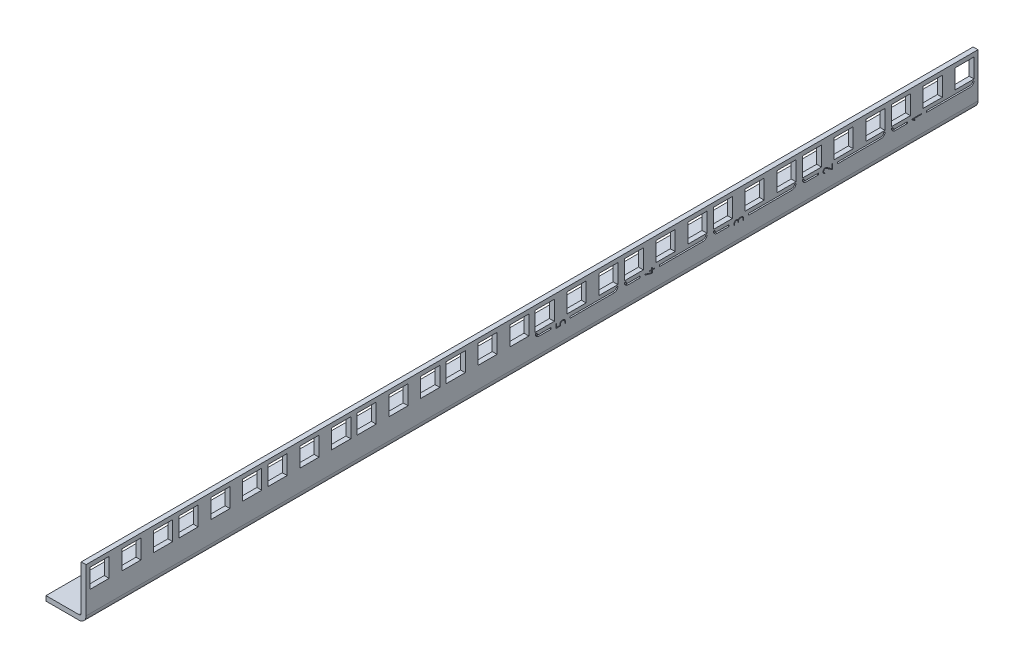
SolidWorks part; units mm, degrees
ref_plane "Front Plane" through (0, 0, 0) normal (0, 0, 1) x (1, 0, 0)
ref_plane "Top Plane" through (0, 0, 0) normal (0, 1, 0) x (1, 0, 0)
ref_plane "Right Plane" through (0, 0, 0) normal (1, 0, 0) x (0, 0, -1)
ref_plane "Plane1" through (0, 25.781, 0) normal (0, 1, 0) x (1, 0, 0)
sketch "Sketch1" plane through (0, 25.781, 0) normal (0, 1, 0) x (1, 0, 0)
  line L0 (-25.4, -222.631) -> (25.4, -222.631)
  line L1 (25.4, -222.631) -> (25.4, 222.631)
  line L2 (25.4, 222.631) -> (-25.4, 222.631)
  line L3 (-25.4, 222.631) -> (-25.4, -222.631)
extrude "Boss-Extrude1" add sketch "Sketch1" against normal blind 25.781
sketch "Sketch2" plane through (0, 0, -222.631) normal (0, 0, -1) x (-1, 0, 0)
  line L0 (25.4, 25.781) -> (-22.987, 25.781)
  line L1 (-22.987, 25.781) -> (-22.987, 2.413)
  line L2 (-22.987, 2.413) -> (25.4, 2.413)
  line L3 (25.4, 2.413) -> (25.4, 25.781)
extrude "Cut-Extrude1" cut sketch "Sketch2" against normal through all
sketch "Sketch3" plane through (0, 0, 0) normal (0, -1, 0) x (1, 0, 0)
  line L0 (-13.5001, -198.0311) -> (-8.7503, -198.0311)
  line L1 (-8.7503, -190.0809) -> (-13.5001, -190.0809)
  arc A0 (-8.7503, -198.0311) -> (-8.7503, -190.0809) centre (-8.7503, -194.056) ccw
  arc A1 (-13.5001, -190.0809) -> (-13.5001, -198.0311) centre (-13.5001, -194.056) ccw
extrude "Cut-Extrude2" cut sketch "Sketch3" against normal through all
sketch "Sketch4" plane through (22.987, 0, 0) normal (-1, 0, 0) x (0, 0, 1)
  line L0 (220.6625, 23.6474) -> (211.1375, 23.6474)
  line L1 (211.1375, 23.6474) -> (211.1375, 14.1224)
  line L2 (211.1375, 14.1224) -> (220.6625, 14.1224)
  line L3 (220.6625, 14.1224) -> (220.6625, 23.6474)
extrude "Cut-Extrude3" cut sketch "Sketch4" against normal through all
sketch "Sketch5" plane through (22.987, 0, 0) normal (-1, 0, 0) x (0, 0, 1)
  line L0 (204.7875, 23.6474) -> (195.2625, 23.6474)
  line L1 (195.2625, 23.6474) -> (195.2625, 14.1224)
  line L2 (195.2625, 14.1224) -> (204.7875, 14.1224)
  line L3 (204.7875, 14.1224) -> (204.7875, 23.6474)
extrude "Cut-Extrude4" cut sketch "Sketch5" against normal through all
sketch "Sketch6" plane through (22.987, 0, 0) normal (-1, 0, 0) x (0, 0, 1)
  line L0 (188.9125, 23.6474) -> (179.3875, 23.6474)
  line L1 (179.3875, 23.6474) -> (179.3875, 14.1224)
  line L2 (179.3875, 14.1224) -> (188.9125, 14.1224)
  line L3 (188.9125, 14.1224) -> (188.9125, 23.6474)
extrude "Cut-Extrude5" cut sketch "Sketch6" against normal through all
sketch "Sketch7" plane through (22.987, 0, 0) normal (-1, 0, 0) x (0, 0, 1)
  line L0 (176.2125, 23.6474) -> (166.6875, 23.6474)
  line L1 (166.6875, 23.6474) -> (166.6875, 14.1224)
  line L2 (166.6875, 14.1224) -> (176.2125, 14.1224)
  line L3 (176.2125, 14.1224) -> (176.2125, 23.6474)
extrude "Cut-Extrude6" cut sketch "Sketch7" against normal through all
sketch "Sketch8" plane through (22.987, 0, 0) normal (-1, 0, 0) x (0, 0, 1)
  line L0 (160.3375, 23.6474) -> (150.8125, 23.6474)
  line L1 (150.8125, 23.6474) -> (150.8125, 14.1224)
  line L2 (150.8125, 14.1224) -> (160.3375, 14.1224)
  line L3 (160.3375, 14.1224) -> (160.3375, 23.6474)
extrude "Cut-Extrude7" cut sketch "Sketch8" against normal through all
sketch "Sketch9" plane through (22.987, 0, 0) normal (-1, 0, 0) x (0, 0, 1)
  line L0 (144.4625, 23.6474) -> (134.9375, 23.6474)
  line L1 (134.9375, 23.6474) -> (134.9375, 14.1224)
  line L2 (134.9375, 14.1224) -> (144.4625, 14.1224)
  line L3 (144.4625, 14.1224) -> (144.4625, 23.6474)
extrude "Cut-Extrude8" cut sketch "Sketch9" against normal through all
sketch "Sketch10" plane through (22.987, 0, 0) normal (-1, 0, 0) x (0, 0, 1)
  line L0 (131.7625, 23.6474) -> (122.2375, 23.6474)
  line L1 (122.2375, 23.6474) -> (122.2375, 14.1224)
  line L2 (122.2375, 14.1224) -> (131.7625, 14.1224)
  line L3 (131.7625, 14.1224) -> (131.7625, 23.6474)
extrude "Cut-Extrude9" cut sketch "Sketch10" against normal through all
sketch "Sketch11" plane through (22.987, 0, 0) normal (-1, 0, 0) x (0, 0, 1)
  line L0 (115.8875, 23.6474) -> (106.3625, 23.6474)
  line L1 (106.3625, 23.6474) -> (106.3625, 14.1224)
  line L2 (106.3625, 14.1224) -> (115.8875, 14.1224)
  line L3 (115.8875, 14.1224) -> (115.8875, 23.6474)
extrude "Cut-Extrude10" cut sketch "Sketch11" against normal through all
sketch "Sketch12" plane through (22.987, 0, 0) normal (-1, 0, 0) x (0, 0, 1)
  line L0 (100.0125, 23.6474) -> (90.4875, 23.6474)
  line L1 (90.4875, 23.6474) -> (90.4875, 14.1224)
  line L2 (90.4875, 14.1224) -> (100.0125, 14.1224)
  line L3 (100.0125, 14.1224) -> (100.0125, 23.6474)
extrude "Cut-Extrude11" cut sketch "Sketch12" against normal through all
sketch "Sketch13" plane through (22.987, 0, 0) normal (-1, 0, 0) x (0, 0, 1)
  line L0 (87.3125, 23.6474) -> (77.7875, 23.6474)
  line L1 (77.7875, 23.6474) -> (77.7875, 14.1224)
  line L2 (77.7875, 14.1224) -> (87.3125, 14.1224)
  line L3 (87.3125, 14.1224) -> (87.3125, 23.6474)
extrude "Cut-Extrude12" cut sketch "Sketch13" against normal through all
sketch "Sketch14" plane through (22.987, 0, 0) normal (-1, 0, 0) x (0, 0, 1)
  line L0 (71.4375, 23.6474) -> (61.9125, 23.6474)
  line L1 (61.9125, 23.6474) -> (61.9125, 14.1224)
  line L2 (61.9125, 14.1224) -> (71.4375, 14.1224)
  line L3 (71.4375, 14.1224) -> (71.4375, 23.6474)
extrude "Cut-Extrude13" cut sketch "Sketch14" against normal through all
sketch "Sketch15" plane through (22.987, 0, 0) normal (-1, 0, 0) x (0, 0, 1)
  line L0 (55.5625, 23.6474) -> (46.0375, 23.6474)
  line L1 (46.0375, 23.6474) -> (46.0375, 14.1224)
  line L2 (46.0375, 14.1224) -> (55.5625, 14.1224)
  line L3 (55.5625, 14.1224) -> (55.5625, 23.6474)
extrude "Cut-Extrude14" cut sketch "Sketch15" against normal through all
sketch "Sketch16" plane through (22.987, 0, 0) normal (-1, 0, 0) x (0, 0, 1)
  line L0 (42.8625, 23.6474) -> (33.3375, 23.6474)
  line L1 (33.3375, 23.6474) -> (33.3375, 14.1224)
  line L2 (33.3375, 14.1224) -> (42.8625, 14.1224)
  line L3 (42.8625, 14.1224) -> (42.8625, 23.6474)
extrude "Cut-Extrude15" cut sketch "Sketch16" against normal through all
sketch "Sketch17" plane through (22.987, 0, 0) normal (-1, 0, 0) x (0, 0, 1)
  line L0 (26.9875, 23.6474) -> (17.4625, 23.6474)
  line L1 (17.4625, 23.6474) -> (17.4625, 14.1224)
  line L2 (17.4625, 14.1224) -> (26.9875, 14.1224)
  line L3 (26.9875, 14.1224) -> (26.9875, 23.6474)
extrude "Cut-Extrude16" cut sketch "Sketch17" against normal through all
sketch "Sketch18" plane through (22.987, 0, 0) normal (-1, 0, 0) x (0, 0, 1)
  line L0 (11.1125, 23.6474) -> (1.5875, 23.6474)
  line L1 (1.5875, 23.6474) -> (1.5875, 14.1224)
  line L2 (1.5875, 14.1224) -> (11.1125, 14.1224)
  line L3 (11.1125, 14.1224) -> (11.1125, 23.6474)
extrude "Cut-Extrude17" cut sketch "Sketch18" against normal through all
sketch "Sketch19" plane through (22.987, 0, 0) normal (-1, 0, 0) x (0, 0, 1)
  line L0 (-1.5875, 23.6474) -> (-11.1125, 23.6474)
  line L1 (-11.1125, 23.6474) -> (-11.1125, 14.1224)
  line L2 (-11.1125, 14.1224) -> (-1.5875, 14.1224)
  line L3 (-1.5875, 14.1224) -> (-1.5875, 23.6474)
extrude "Cut-Extrude18" cut sketch "Sketch19" against normal through all
sketch "Sketch20" plane through (22.987, 0, 0) normal (-1, 0, 0) x (0, 0, 1)
  line L0 (-17.4625, 23.6474) -> (-26.9875, 23.6474)
  line L1 (-26.9875, 23.6474) -> (-26.9875, 14.1224)
  line L2 (-26.9875, 14.1224) -> (-17.4625, 14.1224)
  line L3 (-17.4625, 14.1224) -> (-17.4625, 23.6474)
extrude "Cut-Extrude19" cut sketch "Sketch20" against normal through all
sketch "Sketch21" plane through (22.987, 0, 0) normal (-1, 0, 0) x (0, 0, 1)
  line L0 (-33.3375, 23.6474) -> (-42.8625, 23.6474)
  line L1 (-42.8625, 23.6474) -> (-42.8625, 14.1224)
  line L2 (-42.8625, 14.1224) -> (-33.3375, 14.1224)
  line L3 (-33.3375, 14.1224) -> (-33.3375, 23.6474)
extrude "Cut-Extrude20" cut sketch "Sketch21" against normal through all
sketch "Sketch22" plane through (22.987, 0, 0) normal (-1, 0, 0) x (0, 0, 1)
  line L0 (-46.0375, 23.6474) -> (-55.5625, 23.6474)
  line L1 (-55.5625, 23.6474) -> (-55.5625, 14.1224)
  line L2 (-55.5625, 14.1224) -> (-46.0375, 14.1224)
  line L3 (-46.0375, 14.1224) -> (-46.0375, 23.6474)
extrude "Cut-Extrude21" cut sketch "Sketch22" against normal through all
sketch "Sketch23" plane through (22.987, 0, 0) normal (-1, 0, 0) x (0, 0, 1)
  line L0 (-61.9125, 23.6474) -> (-71.4375, 23.6474)
  line L1 (-71.4375, 23.6474) -> (-71.4375, 14.1224)
  line L2 (-71.4375, 14.1224) -> (-61.9125, 14.1224)
  line L3 (-61.9125, 14.1224) -> (-61.9125, 23.6474)
extrude "Cut-Extrude22" cut sketch "Sketch23" against normal through all
sketch "Sketch24" plane through (22.987, 0, 0) normal (-1, 0, 0) x (0, 0, 1)
  line L0 (-77.7875, 23.6474) -> (-87.3125, 23.6474)
  line L1 (-87.3125, 23.6474) -> (-87.3125, 14.1224)
  line L2 (-87.3125, 14.1224) -> (-77.7875, 14.1224)
  line L3 (-77.7875, 14.1224) -> (-77.7875, 23.6474)
extrude "Cut-Extrude23" cut sketch "Sketch24" against normal through all
sketch "Sketch25" plane through (22.987, 0, 0) normal (-1, 0, 0) x (0, 0, 1)
  line L0 (-90.4875, 23.6474) -> (-100.0125, 23.6474)
  line L1 (-100.0125, 23.6474) -> (-100.0125, 14.1224)
  line L2 (-100.0125, 14.1224) -> (-90.4875, 14.1224)
  line L3 (-90.4875, 14.1224) -> (-90.4875, 23.6474)
extrude "Cut-Extrude24" cut sketch "Sketch25" against normal through all
sketch "Sketch26" plane through (22.987, 0, 0) normal (-1, 0, 0) x (0, 0, 1)
  line L0 (-106.3625, 23.6474) -> (-115.8875, 23.6474)
  line L1 (-115.8875, 23.6474) -> (-115.8875, 14.1224)
  line L2 (-115.8875, 14.1224) -> (-106.3625, 14.1224)
  line L3 (-106.3625, 14.1224) -> (-106.3625, 23.6474)
extrude "Cut-Extrude25" cut sketch "Sketch26" against normal through all
sketch "Sketch27" plane through (22.987, 0, 0) normal (-1, 0, 0) x (0, 0, 1)
  line L0 (-122.2375, 23.6474) -> (-131.7625, 23.6474)
  line L1 (-131.7625, 23.6474) -> (-131.7625, 14.1224)
  line L2 (-131.7625, 14.1224) -> (-122.2375, 14.1224)
  line L3 (-122.2375, 14.1224) -> (-122.2375, 23.6474)
extrude "Cut-Extrude26" cut sketch "Sketch27" against normal through all
sketch "Sketch28" plane through (22.987, 0, 0) normal (-1, 0, 0) x (0, 0, 1)
  line L0 (-134.9375, 23.6474) -> (-144.4625, 23.6474)
  line L1 (-144.4625, 23.6474) -> (-144.4625, 14.1224)
  line L2 (-144.4625, 14.1224) -> (-134.9375, 14.1224)
  line L3 (-134.9375, 14.1224) -> (-134.9375, 23.6474)
extrude "Cut-Extrude27" cut sketch "Sketch28" against normal through all
sketch "Sketch29" plane through (22.987, 0, 0) normal (-1, 0, 0) x (0, 0, 1)
  line L0 (-150.8125, 23.6474) -> (-160.3375, 23.6474)
  line L1 (-160.3375, 23.6474) -> (-160.3375, 14.1224)
  line L2 (-160.3375, 14.1224) -> (-150.8125, 14.1224)
  line L3 (-150.8125, 14.1224) -> (-150.8125, 23.6474)
extrude "Cut-Extrude28" cut sketch "Sketch29" against normal through all
sketch "Sketch30" plane through (22.987, 0, 0) normal (-1, 0, 0) x (0, 0, 1)
  line L0 (-166.6875, 23.6474) -> (-176.2125, 23.6474)
  line L1 (-176.2125, 23.6474) -> (-176.2125, 14.1224)
  line L2 (-176.2125, 14.1224) -> (-166.6875, 14.1224)
  line L3 (-166.6875, 14.1224) -> (-166.6875, 23.6474)
extrude "Cut-Extrude29" cut sketch "Sketch30" against normal through all
sketch "Sketch31" plane through (22.987, 0, 0) normal (-1, 0, 0) x (0, 0, 1)
  line L0 (-179.3875, 23.6474) -> (-188.9125, 23.6474)
  line L1 (-188.9125, 23.6474) -> (-188.9125, 14.1224)
  line L2 (-188.9125, 14.1224) -> (-179.3875, 14.1224)
  line L3 (-179.3875, 14.1224) -> (-179.3875, 23.6474)
extrude "Cut-Extrude30" cut sketch "Sketch31" against normal through all
sketch "Sketch32" plane through (22.987, 0, 0) normal (-1, 0, 0) x (0, 0, 1)
  line L0 (-195.2625, 23.6474) -> (-204.7875, 23.6474)
  line L1 (-204.7875, 23.6474) -> (-204.7875, 14.1224)
  line L2 (-204.7875, 14.1224) -> (-195.2625, 14.1224)
  line L3 (-195.2625, 14.1224) -> (-195.2625, 23.6474)
extrude "Cut-Extrude31" cut sketch "Sketch32" against normal through all
sketch "Sketch33" plane through (22.987, 0, 0) normal (-1, 0, 0) x (0, 0, 1)
  line L0 (-211.1375, 23.6474) -> (-220.6625, 23.6474)
  line L1 (-220.6625, 23.6474) -> (-220.6625, 14.1224)
  line L2 (-220.6625, 14.1224) -> (-211.1375, 14.1224)
  line L3 (-211.1375, 14.1224) -> (-211.1375, 23.6474)
extrude "Cut-Extrude32" cut sketch "Sketch33" against normal through all
sketch "Sketch34" plane through (0, 2.413, 0) normal (0, 1, 0) x (-1, 0, 0)
  line L0 (13.5001, 198.0311) -> (8.7503, 198.0311)
  line L1 (8.7503, 190.0809) -> (13.5001, 190.0809)
  arc A0 (8.7503, 198.0311) -> (8.7503, 190.0809) centre (8.7503, 194.056) ccw
  arc A1 (13.5001, 190.0809) -> (13.5001, 198.0311) centre (13.5001, 194.056) ccw
extrude "Cut-Extrude33" cut sketch "Sketch34" against normal through all
sketch "Sketch35" plane through (25.4, 0, 0) normal (1, 0, 0) x (0, 0, -1)
  line L0 (61.1315, 11.8809) -> (61.1315, 12.2306)
  line L1 (61.1315, 12.2306) -> (60.031, 12.2306)
  line L2 (60.031, 12.2306) -> (60.031, 12.9703)
  line L3 (60.031, 12.9703) -> (59.6666, 12.9703)
  line L4 (59.6666, 12.9703) -> (59.6666, 12.2306)
  line L5 (59.6666, 12.2306) -> (58.6471, 12.2306)
  line L6 (58.6471, 12.2306) -> (58.6471, 11.8809)
  line L7 (58.6471, 11.8809) -> (59.6666, 11.8809)
  line L8 (59.6666, 11.8809) -> (59.6666, 10.8394)
  line L9 (59.6666, 10.8394) -> (56.3726, 11.8368)
  line L10 (56.3726, 11.8368) -> (56.3689, 11.4761)
  line L11 (56.3689, 11.4761) -> (59.7182, 10.4713)
  line L12 (59.7182, 10.4713) -> (60.031, 10.4713)
  line L13 (60.031, 10.4713) -> (60.031, 11.8809)
  line L14 (60.031, 11.8809) -> (61.1315, 11.8809)
extrude "Cut-Extrude34" cut sketch "Sketch35" against normal blind 0.762
sketch "Sketch36" plane through (25.4, 0, 0) normal (1, 0, 0) x (0, 0, -1)
  line L0 (16.3428, 10.5431) -> (16.6814, 10.5431)
  line L1 (13.899, 10.9332) -> (12.2539, 10.9332)
  line L2 (12.2539, 10.9332) -> (12.2539, 12.5747)
  line L3 (12.2539, 12.5747) -> (11.9189, 12.5747)
  line L4 (11.9189, 12.5747) -> (11.9189, 10.5946)
  line L5 (11.9189, 10.5946) -> (14.234, 10.5946)
  spline S0 degree 3 poles (16.3428, 10.5431) (16.3428, 10.8445) (16.3687, 11.1477) (16.3359, 11.4474) (16.3241, 11.5549) (16.2955, 11.6626) (16.2478, 11.7598) (16.1999, 11.8573) (16.1312, 11.9465) (16.0508, 12.0197) (15.9605, 12.1018) (15.8543, 12.1688) (15.7419, 12.2167) (15.6292, 12.2647) (15.5076, 12.2943) (15.3859, 12.3078) (15.2464, 12.3232) (15.1023, 12.3213) (14.9651, 12.2916) (14.8612, 12.269) (14.7594, 12.2294) (14.6684, 12.1744) (14.577, 12.1192) (14.4936, 12.0464) (14.4296, 11.9609) (14.3732, 11.8857) (14.3299, 11.7996) (14.2997, 11.7105) (14.2545, 11.5774) (14.2363, 11.4345) (14.2341, 11.2939) (14.2323, 11.1774) (14.2329, 11.0608) (14.2331, 10.9443) (14.2334, 10.8277) (14.234, 10.7112) (14.234, 10.5946) knots 0 0 0 0 0.000904 0.000904 0.000904 0.001232 0.001232 0.001232 0.001561 0.001561 0.001561 0.001931 0.001931 0.001931 0.002301 0.002301 0.002301 0.002725 0.002725 0.002725 0.003045 0.003045 0.003045 0.003369 0.003369 0.003369 0.003651 0.003651 0.003651 0.004075 0.004075 0.004075 0.004423 0.004423 0.004423 0.004772 0.004772 0.004772 0.004772
  spline S1 degree 3 poles (15.213, 12.652) (15.4155, 12.652) (15.6221, 12.6283) (15.8143, 12.5643) (15.9431, 12.5214) (16.0675, 12.4588) (16.1758, 12.377) (16.2844, 12.2948) (16.379, 12.1912) (16.453, 12.0769) (16.5425, 11.9387) (16.6077, 11.7824) (16.6461, 11.6222) (16.7299, 11.2722) (16.6814, 10.903) (16.6814, 10.5431) knots 0 0 0 0 0.000608 0.000608 0.000608 0.001013 0.001013 0.001013 0.001421 0.001421 0.001421 0.001914 0.001914 0.001914 0.003 0.003 0.003 0.003
  spline S2 degree 3 poles (13.899, 10.9332) (13.899, 11.1689) (13.8803, 11.4071) (13.9151, 11.6402) (13.9339, 11.7666) (13.9717, 11.8922) (14.0302, 12.0058) (14.0888, 12.1199) (14.1698, 12.2242) (14.2639, 12.3114) (14.3547, 12.3956) (14.4594, 12.4671) (14.5713, 12.5203) (14.695, 12.579) (14.83, 12.6165) (14.9656, 12.6355) (15.0474, 12.6469) (15.1303, 12.652) (15.213, 12.652) knots 0 0 0 0 0.000707 0.000707 0.000707 0.001092 0.001092 0.001092 0.001479 0.001479 0.001479 0.001852 0.001852 0.001852 0.002264 0.002264 0.002264 0.002511 0.002511 0.002511 0.002511
extrude "Cut-Extrude35" cut sketch "Sketch36" against normal blind 0.762
sketch "Sketch37" plane through (25.4, 0, 0) normal (1, 0, 0) x (0, 0, -1)
  line L0 (150.0314, 12.8931) -> (149.6947, 12.8931)
  line L1 (149.6947, 12.8931) -> (149.6947, 10.8432)
  line L2 (149.6947, 10.8432) -> (146.9162, 12.7321)
  line L3 (146.3525, 10.4076) -> (146.3525, 10.748)
  line L4 (149.6983, 10.4368) -> (150.0314, 10.4222)
  line L5 (150.0314, 10.4222) -> (150.0314, 12.8931)
  spline S0 degree 3 poles (146.3525, 10.4076) (146.1386, 10.4564) (145.9244, 10.5328) (145.743, 10.6562) (145.6457, 10.7224) (145.5567, 10.804) (145.4858, 10.8977) (145.4146, 10.9919) (145.3602, 11.1006) (145.3253, 11.2133) (145.2819, 11.3538) (145.267, 11.5039) (145.2692, 11.651) (145.2721, 11.8451) (145.2993, 12.044) (145.3712, 12.2243) (145.4116, 12.3258) (145.4676, 12.4229) (145.5382, 12.5062) (145.6091, 12.5899) (145.6963, 12.6621) (145.7921, 12.7155) (145.8817, 12.7654) (145.9806, 12.8004) (146.081, 12.822) (146.2419, 12.8566) (146.4116, 12.8637) (146.5746, 12.8402) (146.6928, 12.8231) (146.8099, 12.7865) (146.9162, 12.7321) knots 0 0 0 0 0.000658 0.000658 0.000658 0.001008 0.001008 0.001008 0.001359 0.001359 0.001359 0.001796 0.001796 0.001796 0.002376 0.002376 0.002376 0.002699 0.002699 0.002699 0.003024 0.003024 0.003024 0.003327 0.003327 0.003327 0.003815 0.003815 0.003815 0.004169 0.004169 0.004169 0.004169
  spline S1 degree 3 poles (145.829, 12.3404) (145.7581, 12.2492) (145.6979, 12.1462) (145.6632, 12.036) (145.6176, 11.8912) (145.5982, 11.7364) (145.6025, 11.5847) (145.6051, 11.4931) (145.6201, 11.4004) (145.6508, 11.3141) (145.6817, 11.2273) (145.7298, 11.1449) (145.7901, 11.0752) (145.8448, 11.0121) (145.9101, 10.9576) (145.9802, 10.9122) (146.094, 10.8385) (146.2224, 10.7863) (146.3525, 10.748) knots 0 0 0 0 0.000347 0.000347 0.000347 0.0008 0.0008 0.0008 0.001073 0.001073 0.001073 0.001349 0.001349 0.001349 0.001597 0.001597 0.001597 0.002002 0.002002 0.002002 0.002002
  spline S2 degree 3 poles (149.6983, 10.4368) (149.3691, 10.6598) (149.0399, 10.8829) (148.7106, 11.1059) (148.3814, 11.3289) (148.0521, 11.5519) (147.7229, 11.7749) (147.534, 11.9028) (147.345, 12.0308) (147.1561, 12.1588) (146.9665, 12.2872) (146.7804, 12.4438) (146.5573, 12.4954) (146.4525, 12.5197) (146.3418, 12.5271) (146.2351, 12.513) (146.1476, 12.5014) (146.0609, 12.474) (145.9823, 12.4337) (145.9291, 12.4064) (145.88, 12.3717) (145.829, 12.3404) knots 0 0 0 0 0.001193 0.001193 0.001193 0.002386 0.002386 0.002386 0.00307 0.00307 0.00307 0.00376 0.00376 0.00376 0.004075 0.004075 0.004075 0.004334 0.004334 0.004334 0.004507 0.004507 0.004507 0.004507
extrude "Cut-Extrude36" cut sketch "Sketch37" against normal blind 0.762
sketch "Sketch38" plane through (25.4, 0, 0) normal (1, 0, 0) x (0, 0, -1)
  line L0 (105.2428, 10.6277) -> (105.5814, 10.6277)
  line L1 (100.8189, 10.6204) -> (101.1539, 10.6204)
  line L2 (102.7843, 10.9443) -> (103.1229, 10.9443)
  spline S0 degree 3 poles (105.2428, 10.6277) (105.2428, 10.9248) (105.274, 11.2247) (105.2319, 11.5187) (105.217, 11.623) (105.1849, 11.7267) (105.1352, 11.8196) (105.0854, 11.9127) (105.0166, 11.9972) (104.9375, 12.0671) (104.8627, 12.1332) (104.777, 12.1886) (104.6859, 12.2295) (104.5845, 12.275) (104.4745, 12.3036) (104.3642, 12.3174) (104.1886, 12.3393) (104.0063, 12.3309) (103.8339, 12.2909) (103.7244, 12.2655) (103.6167, 12.2242) (103.5205, 12.1659) (103.4408, 12.1176) (103.3666, 12.0571) (103.3068, 11.9856) (103.2466, 11.9137) (103.1998, 11.8287) (103.17, 11.7398) (103.1367, 11.6405) (103.1229, 11.5339) (103.1229, 11.4291) (103.1229, 11.2675) (103.1229, 11.1059) (103.1229, 10.9443) knots 0 0 0 0 0.000891 0.000891 0.000891 0.001209 0.001209 0.001209 0.001528 0.001528 0.001528 0.001828 0.001828 0.001828 0.002163 0.002163 0.002163 0.002698 0.002698 0.002698 0.003037 0.003037 0.003037 0.003317 0.003317 0.003317 0.0036 0.0036 0.0036 0.003915 0.003915 0.003915 0.004396 0.004396 0.004396 0.004396
  spline S1 degree 3 poles (104.1976, 12.6667) (104.3916, 12.6667) (104.5898, 12.64) (104.7722, 12.574) (104.9062, 12.5254) (105.034, 12.4541) (105.1448, 12.3644) (105.2558, 12.2745) (105.3531, 12.163) (105.4234, 12.0386) (105.4867, 11.9266) (105.5301, 11.8021) (105.5544, 11.6758) (105.6206, 11.3327) (105.5814, 10.9772) (105.5814, 10.6277) knots 0 0 0 0 0.000582 0.000582 0.000582 0.001008 0.001008 0.001008 0.001436 0.001436 0.001436 0.001819 0.001819 0.001819 0.002863 0.002863 0.002863 0.002863
  spline S2 degree 3 poles (102.9389, 12.0447) (102.9781, 12.1341) (103.035, 12.2173) (103.1032, 12.2871) (103.171, 12.3566) (103.251, 12.415) (103.3355, 12.4629) (103.4794, 12.5443) (103.6398, 12.5994) (103.8021, 12.6308) (103.9321, 12.6559) (104.0652, 12.6667) (104.1976, 12.6667) knots 0 0 0 0 0.000293 0.000293 0.000293 0.000583 0.000583 0.000583 0.001079 0.001079 0.001079 0.001474 0.001474 0.001474 0.001474
  spline S3 degree 3 poles (100.8189, 10.6204) (100.8189, 11.0186) (100.765, 11.4358) (100.8932, 11.8129) (100.9307, 11.923) (100.9858, 12.029) (101.0571, 12.1208) (101.1286, 12.2127) (101.2182, 12.2924) (101.3161, 12.3555) (101.4134, 12.4181) (101.5201, 12.4684) (101.631, 12.5012) (101.7635, 12.5404) (101.9064, 12.5415) (102.0442, 12.5327) (102.175, 12.5244) (102.3076, 12.5061) (102.4309, 12.4616) (102.5342, 12.4243) (102.6322, 12.3675) (102.7166, 12.2971) (102.8027, 12.2253) (102.8771, 12.1382) (102.9389, 12.0447) knots 0 0 0 0 0.001195 0.001195 0.001195 0.001536 0.001536 0.001536 0.001878 0.001878 0.001878 0.002216 0.002216 0.002216 0.002624 0.002624 0.002624 0.00301 0.00301 0.00301 0.003335 0.003335 0.003335 0.003665 0.003665 0.003665 0.003665
  spline S4 degree 3 poles (102.7843, 10.9443) (102.7843, 11.1408) (102.7995, 11.3384) (102.7795, 11.5339) (102.7709, 11.6181) (102.7494, 11.7024) (102.7134, 11.779) (102.6773, 11.8559) (102.6254, 11.9266) (102.5644, 11.9858) (102.5078, 12.0407) (102.443, 12.0885) (102.3732, 12.1252) (102.309, 12.1591) (102.2379, 12.1836) (102.1657, 12.1911) (102.0226, 12.2059) (101.8747, 12.2156) (101.7342, 12.1849) (101.6597, 12.1687) (101.5874, 12.1367) (101.5247, 12.0933) (101.4625, 12.0502) (101.4078, 11.9955) (101.3609, 11.9362) (101.2939, 11.8514) (101.2399, 11.7543) (101.205, 11.6521) (101.1705, 11.5507) (101.1539, 11.442) (101.1539, 11.335) (101.1537, 11.0968) (101.1539, 10.8586) (101.1539, 10.6204) knots 0 0 0 0 0.00059 0.00059 0.00059 0.000846 0.000846 0.000846 0.001103 0.001103 0.001103 0.001341 0.001341 0.001341 0.001561 0.001561 0.001561 0.001991 0.001991 0.001991 0.002218 0.002218 0.002218 0.002443 0.002443 0.002443 0.002765 0.002765 0.002765 0.003083 0.003083 0.003083 0.003784 0.003784 0.003784 0.003784
extrude "Cut-Extrude37" cut sketch "Sketch38" against normal blind 0.762
sketch "Sketch39" plane through (25.4, 0, 0) normal (1, 0, 0) x (0, 0, -1)
  line L0 (191.0996, 11.3191) -> (190.3175, 11.9323)
  line L1 (190.3175, 11.9323) -> (194.4778, 11.9323)
  line L2 (194.4778, 11.9323) -> (194.4814, 12.2665)
  line L3 (194.4814, 12.2665) -> (189.719, 12.2665)
  line L4 (189.719, 12.2665) -> (189.719, 11.9507)
  line L5 (189.719, 11.9507) -> (191.0996, 10.9005)
  line L6 (191.0996, 10.9005) -> (191.0996, 11.3191)
extrude "Cut-Extrude38" cut sketch "Sketch39" against normal blind 0.762
sketch "Sketch40" plane through (25.4, 0, 0) normal (1, 0, 0) x (0, 0, -1)
  line L0 (42.8752, 13.4112) -> (42.1132, 13.4112)
  line L1 (40.9702, 12.2682) -> (19.0627, 12.2682)
  line L2 (19.0627, 12.2682) -> (19.0627, 11.5062)
  line L3 (19.0627, 11.5062) -> (40.9702, 11.5062)
  arc A0 (40.9702, 11.5062) -> (42.8752, 13.4112) centre (40.9702, 13.4112) ccw
  arc A1 (42.1132, 13.4112) -> (40.9702, 12.2682) centre (40.9702, 13.4112) cw
extrude "Cut-Extrude39" cut sketch "Sketch40" against normal blind 0.762
sketch "Sketch41" plane through (25.4, 0, 0) normal (1, 0, 0) x (0, 0, -1)
  line L0 (53.9877, 12.2725) -> (47.8557, 12.2725)
  line L1 (46.8122, 13.4112) -> (46.0502, 13.4112)
  line L2 (47.9552, 11.5062) -> (53.9877, 11.5062)
  line L3 (53.9877, 11.5062) -> (53.9877, 12.2725)
  arc A0 (47.8557, 12.2725) -> (46.8122, 13.4112) centre (47.9552, 13.4112) cw
  arc A1 (46.0502, 13.4112) -> (47.9552, 11.5062) centre (47.9552, 13.4112) ccw
extrude "Cut-Extrude40" cut sketch "Sketch41" against normal blind 0.762
sketch "Sketch42" plane through (25.4, 0, 0) normal (1, 0, 0) x (0, 0, -1)
  line L0 (131.7752, 13.4112) -> (131.0132, 13.4112)
  line L1 (129.8702, 12.2682) -> (107.9627, 12.2682)
  line L2 (107.9627, 12.2682) -> (107.9627, 11.5062)
  line L3 (107.9627, 11.5062) -> (129.8702, 11.5062)
  arc A0 (129.8702, 11.5062) -> (131.7752, 13.4112) centre (129.8702, 13.4112) ccw
  arc A1 (131.0132, 13.4112) -> (129.8702, 12.2682) centre (129.8702, 13.4112) cw
extrude "Cut-Extrude41" cut sketch "Sketch42" against normal blind 0.762
sketch "Sketch43" plane through (25.4, 0, 0) normal (1, 0, 0) x (0, 0, -1)
  line L0 (142.8877, 12.2725) -> (136.7557, 12.2725)
  line L1 (135.7122, 13.4112) -> (134.9502, 13.4112)
  line L2 (136.8552, 11.5062) -> (142.8877, 11.5062)
  line L3 (142.8877, 11.5062) -> (142.8877, 12.2725)
  arc A0 (136.7557, 12.2725) -> (135.7122, 13.4112) centre (136.8552, 13.4112) cw
  arc A1 (134.9502, 13.4112) -> (136.8552, 11.5062) centre (136.8552, 13.4112) ccw
extrude "Cut-Extrude42" cut sketch "Sketch43" against normal blind 0.762
sketch "Sketch44" plane through (25.4, 0, 0) normal (1, 0, 0) x (0, 0, -1)
  line L0 (187.3377, 12.2725) -> (181.2057, 12.2725)
  line L1 (180.1622, 13.4112) -> (179.4002, 13.4112)
  line L2 (181.3052, 11.5062) -> (187.3377, 11.5062)
  line L3 (187.3377, 11.5062) -> (187.3377, 12.2725)
  arc A0 (181.2057, 12.2725) -> (180.1622, 13.4112) centre (181.3052, 13.4112) cw
  arc A1 (179.4002, 13.4112) -> (181.3052, 11.5062) centre (181.3052, 13.4112) ccw
extrude "Cut-Extrude43" cut sketch "Sketch44" against normal blind 0.762
sketch "Sketch45" plane through (25.4, 0, 0) normal (1, 0, 0) x (0, 0, -1)
  line L0 (176.2252, 13.4112) -> (175.4632, 13.4112)
  line L1 (174.3202, 12.2682) -> (152.4127, 12.2682)
  line L2 (152.4127, 12.2682) -> (152.4127, 11.5062)
  line L3 (152.4127, 11.5062) -> (174.3202, 11.5062)
  arc A0 (174.3202, 11.5062) -> (176.2252, 13.4112) centre (174.3202, 13.4112) ccw
  arc A1 (175.4632, 13.4112) -> (174.3202, 12.2682) centre (174.3202, 13.4112) cw
extrude "Cut-Extrude44" cut sketch "Sketch45" against normal blind 0.762
sketch "Sketch46" plane through (25.4, 0, 0) normal (1, 0, 0) x (0, 0, -1)
  line L0 (98.4377, 12.2725) -> (92.3057, 12.2725)
  line L1 (91.2622, 13.4112) -> (90.5002, 13.4112)
  line L2 (92.4052, 11.5062) -> (98.4377, 11.5062)
  line L3 (98.4377, 11.5062) -> (98.4377, 12.2725)
  arc A0 (92.3057, 12.2725) -> (91.2622, 13.4112) centre (92.4052, 13.4112) cw
  arc A1 (90.5002, 13.4112) -> (92.4052, 11.5062) centre (92.4052, 13.4112) ccw
extrude "Cut-Extrude45" cut sketch "Sketch46" against normal blind 0.762
sketch "Sketch47" plane through (25.4, 0, 0) normal (1, 0, 0) x (0, 0, -1)
  line L0 (87.3252, 13.4112) -> (86.5632, 13.4112)
  line L1 (85.4202, 12.2682) -> (63.5127, 12.2682)
  line L2 (63.5127, 12.2682) -> (63.5127, 11.5062)
  line L3 (63.5127, 11.5062) -> (85.4202, 11.5062)
  arc A0 (85.4202, 11.5062) -> (87.3252, 13.4112) centre (85.4202, 13.4112) ccw
  arc A1 (86.5632, 13.4112) -> (85.4202, 12.2682) centre (85.4202, 13.4112) cw
extrude "Cut-Extrude46" cut sketch "Sketch47" against normal blind 0.762
sketch "Sketch48" plane through (25.4, 0, 0) normal (1, 0, 0) x (0, 0, -1)
  line L0 (9.5377, 12.2725) -> (3.4057, 12.2725)
  line L1 (2.3622, 13.4112) -> (1.6002, 13.4112)
  line L2 (3.5052, 11.5062) -> (9.5377, 11.5062)
  line L3 (9.5377, 11.5062) -> (9.5377, 12.2725)
  arc A0 (3.4057, 12.2725) -> (2.3622, 13.4112) centre (3.5052, 13.4112) cw
  arc A1 (1.6002, 13.4112) -> (3.5052, 11.5062) centre (3.5052, 13.4112) ccw
extrude "Cut-Extrude47" cut sketch "Sketch48" against normal blind 0.762
sketch "Sketch49" plane through (25.4, 0, 0) normal (1, 0, 0) x (0, 0, -1)
  line L0 (220.6752, 13.4112) -> (219.9132, 13.4112)
  line L1 (218.7702, 12.2682) -> (196.8627, 12.2682)
  line L2 (196.8627, 12.2682) -> (196.8627, 11.5062)
  line L3 (196.8627, 11.5062) -> (218.7702, 11.5062)
  arc A0 (218.7702, 11.5062) -> (220.6752, 13.4112) centre (218.7702, 13.4112) ccw
  arc A1 (219.9132, 13.4112) -> (218.7702, 12.2682) centre (218.7702, 13.4112) cw
extrude "Cut-Extrude48" cut sketch "Sketch49" against normal blind 0.762
fillet "Fillet1" radius 1.2192 1 edges at (22.987, 2.413, 0)
fillet "Fillet2" radius 3.6322 1 edges at (25.4, 0, 0)
sketch "Sketch50" plane through (-25.4, 0, 0) normal (-1, 0, 0) x (0, 0, 1)
  line L1 (230.4479, 32.9556) -> (-255.2142, 32.9556)
  line L2 (230.4479, 32.9556) -> (230.4479, -45.6842)
  line L3 (230.4479, -45.6842) -> (-255.2142, -45.6842)
  line L4 (-255.2142, 32.9556) -> (-255.2142, -45.6842)
  line L5 (230.4479, 32.9556) -> (-255.2142, -45.6842) construction
  line L6 (230.4479, -45.6842) -> (-255.2142, 32.9556) construction
  point P4 (-12.3831, -6.3643)
extrude "Cut-Extrude49" cut sketch "Sketch50" against normal blind 30.8
